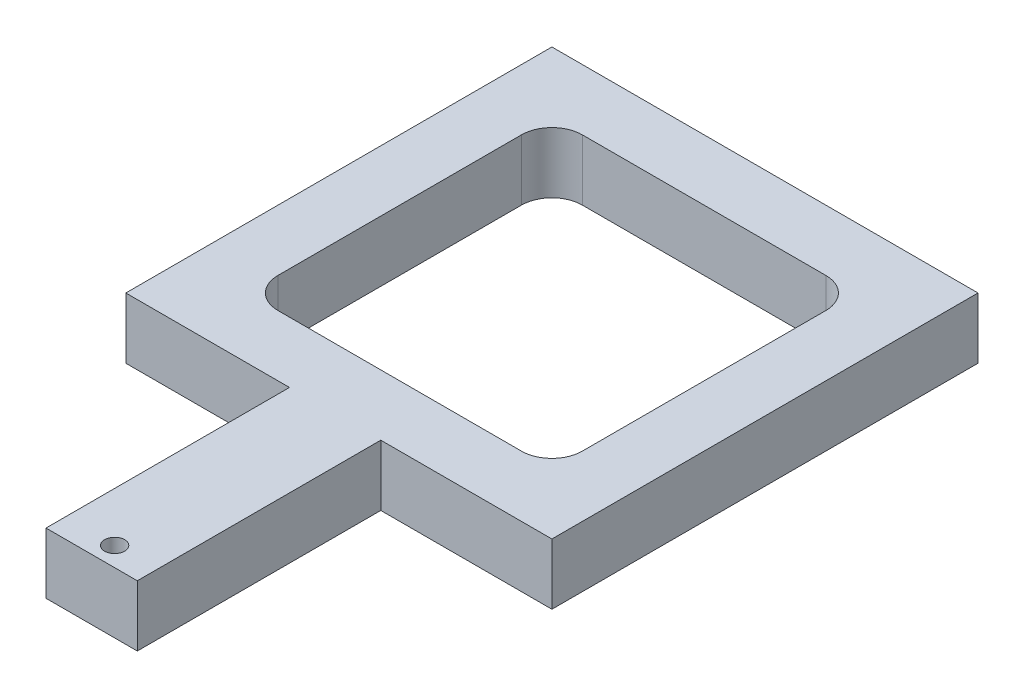
SolidWorks part; units mm, degrees
ref_plane "前视基准面" through (0, 0, 0) normal (0, 0, 1) x (1, 0, 0)
ref_plane "上视基准面" through (0, 0, 0) normal (0, 1, 0) x (1, 0, 0)
ref_plane "右视基准面" through (0, 0, 0) normal (1, 0, 0) x (0, 0, -1)
other "Configuration Table"
sketch "草图1" plane through (0, 0, 0) normal (0, 1, 0) x (1, 0, 0)
  line L0 (-8.1123, -35) -> (-8.1123, -75)
  line L1 (-20, 25) -> (20, 25)
  line L2 (-25, 20) -> (-25, -20)
  line L3 (-20, -25) -> (20, -25)
  line L4 (25, 20) -> (25, -20)
  line L5 (-25, 25) -> (25, -25) construction
  line L6 (-25, -25) -> (25, 25) construction
  line L7 (-35, 35) -> (35, 35)
  line L8 (-35, 35) -> (-35, -35)
  line L9 (-35, -35) -> (-8.1123, -35)
  line L10 (35, 35) -> (35, -35)
  line L11 (-35, 35) -> (35, -35) construction
  line L12 (-35, -35) -> (35, 35) construction
  line L13 (-8.1123, -75) -> (6.8877, -75)
  line L14 (6.8877, -75) -> (6.8877, -35)
  line L15 (6.8877, -35) -> (35, -35)
  arc A0 (20, -25) -> (25, -20) centre (20, -20) ccw
  arc A1 (25, 20) -> (20, 25) centre (20, 20) ccw
  arc A2 (-20, -25) -> (-25, -20) centre (-20, -20) cw
  arc A3 (-25, 20) -> (-20, 25) centre (-20, 20) cw
  point P0 (0, 0)
  point P6 (0, 0)
  dimension "D7" = 5
  dimension "D1" = 10
  dimension "D2" = 10
  dimension "D3" = 50
  dimension "D4" = 50
  dimension "D5" = 15
  dimension "D6" = 40
extrude "凸台-拉伸1" add sketch "草图1" along normal blind 10
sketch "草图2" plane through (0, 10, 0) normal (0, 1, 0) x (1, 0, 0)
  circle A0 centre (0, -71.8381) radius 1.646
extrude "切除-拉伸1" cut sketch "草图2" against normal through all
